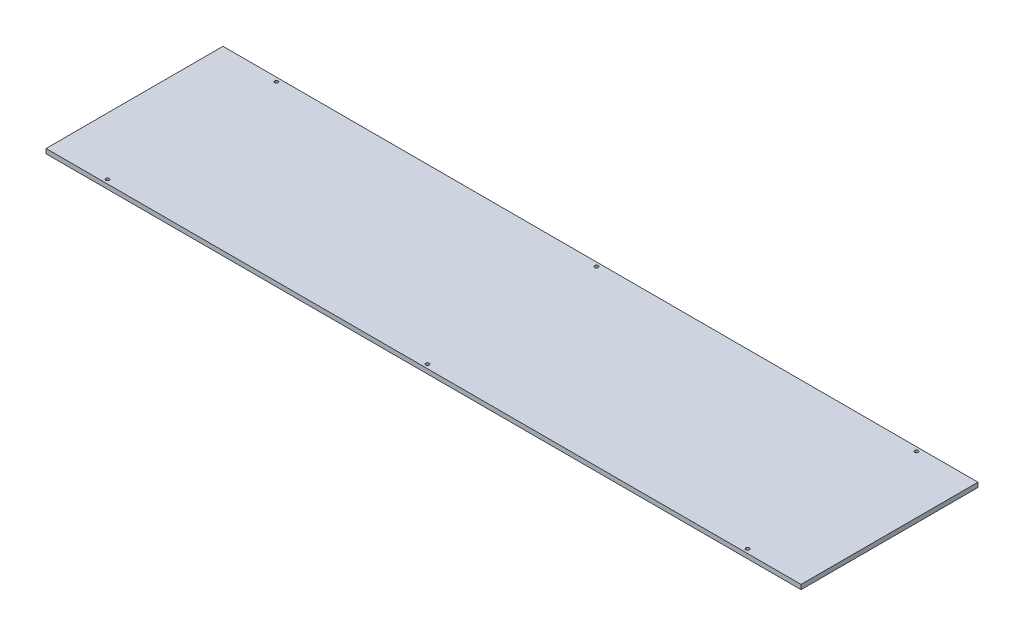
SolidWorks part; units mm, degrees
material "Pine"
ref_plane "Front Plane" through (0, 0, 0) normal (0, 0, 1) x (1, 0, 0)
ref_plane "Top Plane" through (0, 0, 0) normal (0, 1, 0) x (1, 0, 0)
ref_plane "Right Plane" through (0, 0, 0) normal (1, 0, 0) x (0, 0, -1)
sketch "Sketch1" plane through (0, 0, 0) normal (0, 1, 0) x (1, 0, 0)
  line L1 (-306.7465, -74.1935) -> (350.2535, -74.1935)
  line L2 (-306.7465, -74.1935) -> (-306.7465, 79.8065)
  line L3 (-306.7465, 79.8065) -> (350.2535, 79.8065)
  line L4 (350.2535, -74.1935) -> (350.2535, 79.8065)
  circle A0 centre (-256.7465, 76.3065) radius 1.5
  circle A1 centre (21.7535, 76.3065) radius 1.5
  circle A2 centre (300.2535, 76.3065) radius 1.5
  circle A3 centre (300.2535, -70.6935) radius 1.5
  circle A4 centre (21.7535, -70.6935) radius 1.5
  circle A5 centre (-256.7465, -70.6935) radius 1.5
  dimension "D3" = 3
  dimension "D6" = 3
  dimension "D8" = 3
  dimension "D11" = 3
  dimension "D12" = 3
  dimension "D13" = 3
  dimension "D1" = 154
  dimension "D2" = 657
  dimension "D4" = 50
  dimension "D5" = 3.5
  dimension "D7" = 328.5
  dimension "D9" = 50
  dimension "D10" = 3.5
extrude "Boss-Extrude3" add sketch "Sketch1" along normal blind 4
